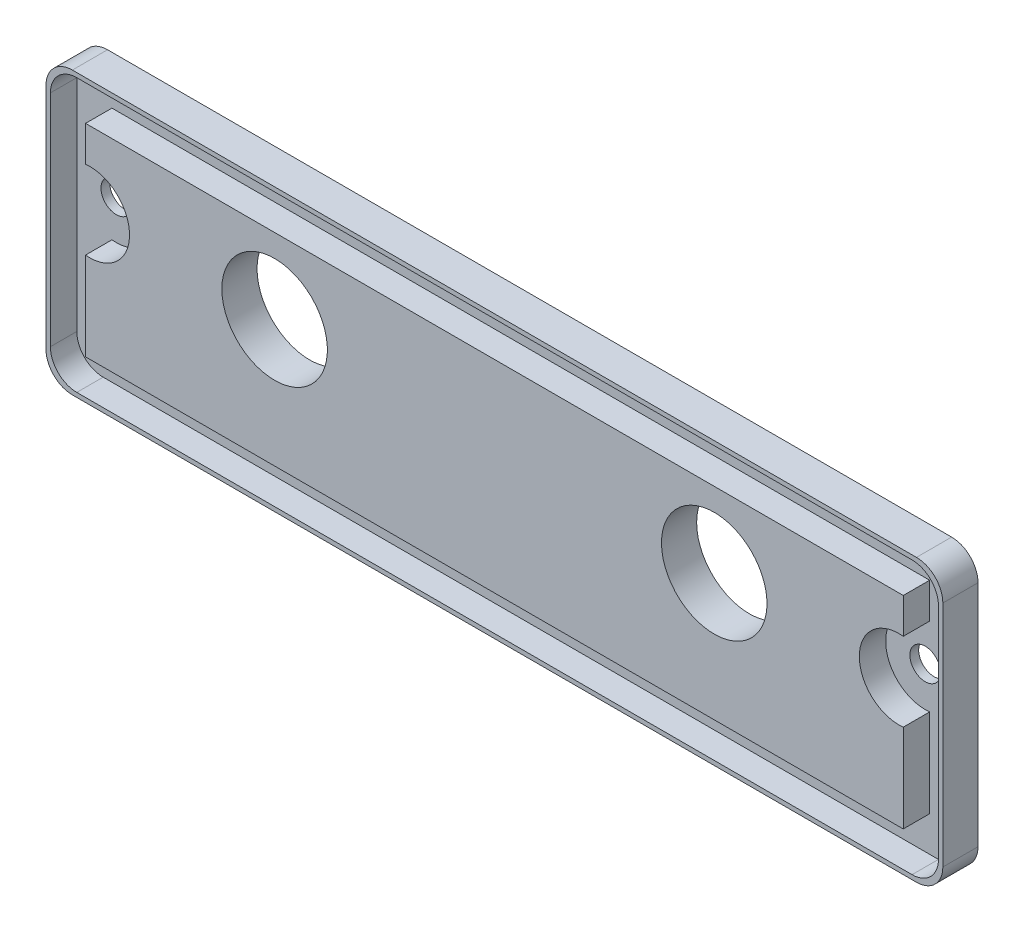
SolidWorks part; units mm, degrees
ref_plane "Front" through (0, 0, 0) normal (0, 0, 1) x (1, 0, 0)
ref_plane "Top" through (0, 0, 0) normal (0, 1, 0) x (1, 0, 0)
ref_plane "Right" through (0, 0, 0) normal (1, 0, 0) x (0, 0, -1)
sketch "Sketch1" plane through (0, 0, 0) normal (0, 0, 1) x (1, 0, 0)
  line L1 (0, 0) -> (-102, 0)
  line L2 (0, 0) -> (0, 32)
  line L3 (0, 32) -> (-102, 32)
  line L4 (-102, 0) -> (-102, 32)
  dimension "D1" = 32
  dimension "D2" = 102
extrude "Boss-Extrude1" add sketch "Sketch1" along normal blind 1
sketch "Sketch2" plane through (0, 0, 1) normal (0, 0, 1) x (1, 0, 0)
  line L0 (-102, 16) -> (0, 16) construction
  line L1 (-102, 32) -> (-102, 0) construction
  line L2 (0, 0) -> (0, 32) construction
  line L3 (0, 16) -> (-51, 32) construction
  line L4 (0, 32) -> (-102, 32) construction
  line L5 (-51, 32) -> (-51, 0) construction
  line L6 (-102, 0) -> (0, 0) construction
  line L7 (-51, 4.5) -> (-51, 27.5) construction
  line L8 (-97.5, 4.5) -> (-4.5, 4.5)
  line L9 (-97.5, 4.5) -> (-97.5, 27.5) construction
  line L10 (-97.5, 27.5) -> (-4.5, 27.5)
  line L11 (-4.5, 4.5) -> (-4.5, 27.5) construction
  line L12 (-51, 27.5) -> (-4.5, 16) construction
  line L13 (-4.5, 16) -> (-97.5, 16) construction
  line L14 (-4.5, 23.4721) -> (-4.5, 27.5)
  line L15 (-102, 32) -> (0, 32)
  line L16 (-102, 32) -> (-102, 0)
  line L17 (-102, 0) -> (0, 0)
  line L18 (0, 32) -> (0, 0)
  line L19 (-4.5, 14.5279) -> (-4.5, 4.5)
  line L20 (-97.5, 27.5) -> (-97.5, 23.4721)
  line L21 (-97.5, 23.4721) -> (-98.5113, 24.5218)
  line L22 (-97.5, 14.5279) -> (-97.5, 4.5)
  line L23 (-101.5, 31.5) -> (-0.5, 31.5)
  line L24 (-101.5, 31.5) -> (-101.5, 0.5)
  line L25 (-101.5, 0.5) -> (-0.5, 0.5)
  line L26 (-0.5, 31.5) -> (-0.5, 0.5)
  line L27 (-97.5, 4.5) -> (-98.4397, 5.5531)
  circle A0 centre (-97, 19) radius 2.25 construction
  circle A1 centre (-5, 19) radius 2.25 construction
  arc A2 (-97.5, 23.4721) -> (-97.5, 14.5279) centre (-97, 19) cw
  arc A3 (-4.5, 23.4721) -> (-4.5, 14.5279) centre (-5, 19) ccw
  dimension "D7" = 4.5
  dimension "D8" = 4.5
  dimension "D13" = 4.5
  dimension "D14" = 4.5
  dimension "D1" = 23
  dimension "D2" = 93
  dimension "D3" = 3
  dimension "D4" = 46
  dimension "D5" = 46
  dimension "D6" = 3
  dimension "D9" = 0.5
  dimension "D10" = 0.5
  dimension "D11" = 0.5
  dimension "D12" = 0.5
extrude "Boss-Extrude2" add sketch "Sketch2" along normal blind 3
sketch "Sketch3" plane through (0, 0, 1) normal (0, 0, 1) x (1, 0, 0)
  line L0 (-83.1296, 19) -> (-115.6197, 19) construction
  line L1 (-115.6197, 19) -> (4.7145, 19) construction
  line L4 (-51, 32) -> (-51, 0) construction
  line L5 (0, 32) -> (-102, 32) construction
  line L6 (-102, 0) -> (0, 0) construction
  circle A0 centre (-97, 19) radius 1.75
  circle A1 centre (-5, 19) radius 1.75
  dimension "D4" = 46
  dimension "D1" = 3.5
  dimension "D2" = 3.5
  dimension "D3" = 92
extrude "Cut-Extrude1" cut sketch "Sketch3" against normal through all
fillet "Fillet1" radius 3 8 edges at (-0.5, 31.5, 2.5) (-0.5, 0.5, 2.5) (-101.5, 0.5, 2.5) (-101.5, 31.5, 2.5) (0, 0, 2) (0, 32, 2) (-102, 32, 2) (-102, 0, 2)
sketch "Sketch4" plane through (0, 0, 0) normal (0, 0, -1) x (-1, 0, 0)
  line L0 (-7.3935, 18.94) -> (115.9821, 18.94) construction
  line L1 (99, 0) -> (3, 0) construction
  line L2 (51, 32) -> (51, 0) construction
  line L3 (3, 32) -> (99, 32) construction
  circle A0 centre (26, 18.94) radius 6
  circle A1 centre (76, 18.94) radius 6
  dimension "D2" = 12
  dimension "D3" = 12
  dimension "D1" = 18.94
  dimension "D4" = 50
  dimension "D5" = 25
extrude "Cut-Extrude2" cut sketch "Sketch4" against normal through all
equation "\"LidMountingHole\"=4.5"
equation "\"D7@Sketch2\"=\"LidMountingHole\""
equation "\"D8@Sketch2\"=\"LidMountingHole\""
equation "\"WallThickness\"= 0.5"
equation "\"D12@Sketch2\"=\"WallThickness\""
equation "\"D11@Sketch2\"=\"WallThickness\""
equation "\"D10@Sketch2\"=\"WallThickness\""
equation "\"D9@Sketch2\"=\"WallThickness\""
equation "\"MountingHoleOffsetX\"=46"
equation "\"D4@Sketch2\"=\"MountingHoleOffsetX\""
equation "\"D5@Sketch2\"=\"MountingHoleOffsetX\""
equation "\"MountingHoleOffsetY\"=3"
equation "\"D6@Sketch2\"=\"MountingHoleOffsetY\""
equation "\"D3@Sketch2\"=\"MountingHoleOffsetY\""
equation "\"Hole\"=3.5"
equation "\"D1@Sketch3\"=\"Hole\""
equation "\"D2@Sketch3\"=\"Hole\""
equation "\"D13@Sketch2\"=\"LidMountingHole\""
equation "\"D14@Sketch2\"=\"LidMountingHole\""
equation "\"ScrewCutOffset\"=46"
equation "\"D3@Sketch3\"=\"ScrewCutOffset\""
equation "\"D4@Sketch3\"=\"ScrewCutOffset\""
